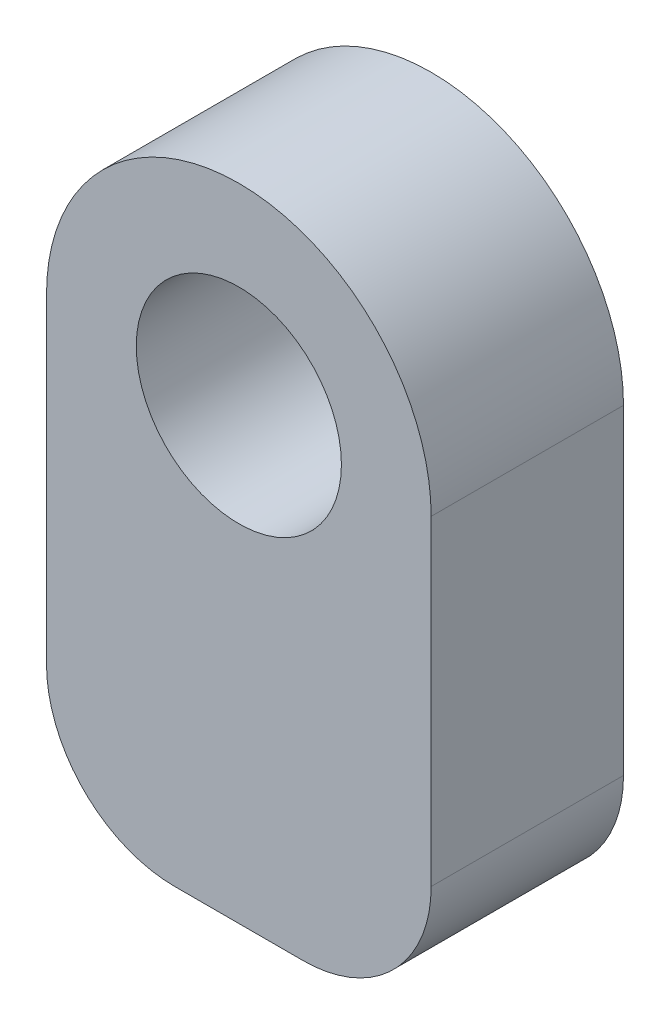
SolidWorks part; units mm, degrees
material "ﾎﾟﾘｶｰﾎﾞﾈｰﾄ(PC)高粘度"
ref_plane "正面" through (0, 0, 0) normal (0, 0, 1) x (1, 0, 0)
ref_plane "平面" through (0, 0, 0) normal (0, 1, 0) x (1, 0, 0)
ref_plane "右側面" through (0, 0, 0) normal (1, 0, 0) x (0, 0, -1)
sketch "ｽｹｯﾁ1" plane through (0, 0, 0) normal (0, 0, 1) x (1, 0, 0)
  line L1 (3, -3.5) -> (-3, -3.5)
  line L2 (3, -3.5) -> (3, 3.5)
  line L4 (-3, -3.5) -> (-3, 3.5)
  line L5 (3, -3.5) -> (-3, 3.5) construction
  line L6 (3, 3.5) -> (-3, -3.5) construction
  arc A0 (-3, 3.5) -> (3, 3.5) centre (0, 3.5) cw
  circle A1 centre (0, 3.5) radius 1.6
  point P0 (0, 0)
  dimension "D3" = 3
  dimension "D4" = 3.2
  dimension "D1" = 6
  dimension "D2" = 7
extrude "ﾎﾞｽ - 押し出し1" add sketch "ｽｹｯﾁ1" along normal blind 3
fillet "ﾌｨﾚｯﾄ1" radius 2 2 edges at (-3, -3.5, 1.5) (3, -3.5, 1.5)
